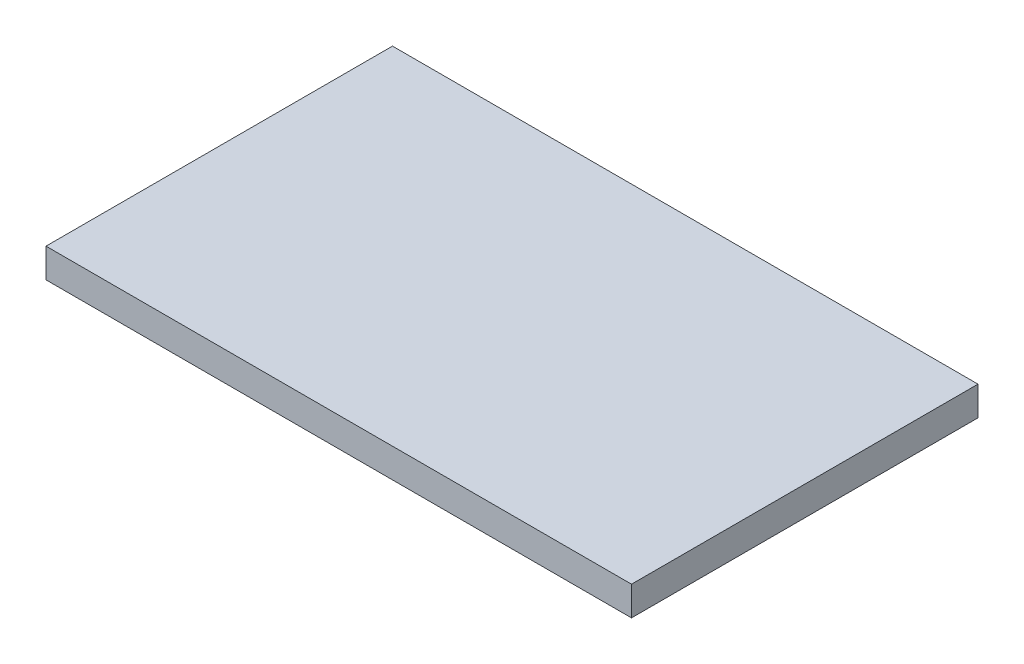
SolidWorks part; units mm, degrees
ref_plane "Front Plane" through (0, 0, 0) normal (0, 0, 1) x (1, 0, 0)
ref_plane "Top Plane" through (0, 0, 0) normal (0, 1, 0) x (1, 0, 0)
ref_plane "Right Plane" through (0, 0, 0) normal (1, 0, 0) x (0, 0, -1)
sketch "Sketch1" plane through (0, 0, 0) normal (0, 0, 1) x (1, 0, 0)
  line L0 (-190.95, -151.5657) -> (-190.95, -142.0407)
  line L1 (-190.95, -250) -> (-190.95, -53.1315) construction
  line L2 (-190.95, -142.0407) -> (190.95, -142.0407)
  line L3 (190.95, -53.1315) -> (190.95, -250) construction
  line L4 (190.95, -142.0407) -> (190.95, -161.0907)
  line L5 (190.95, -161.0907) -> (-190.95, -161.0907)
  line L6 (-190.95, -161.0907) -> (-190.95, -151.5657)
extrude "Boss-Extrude1" add sketch "Sketch1" along normal up to surface (226 mm away)
